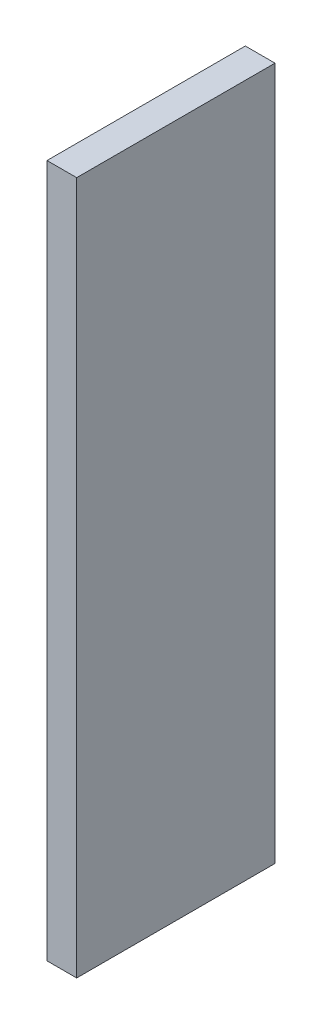
SolidWorks part; units mm, degrees
ref_plane "Front Plane" through (0, 0, 0) normal (0, 0, 1) x (1, 0, 0)
ref_plane "Top Plane" through (0, 0, 0) normal (0, 1, 0) x (1, 0, 0)
ref_plane "Right Plane" through (0, 0, 0) normal (1, 0, 0) x (0, 0, -1)
sketch "Sketch1" plane through (0, 0, 0) normal (1, 0, 0) x (0, 0, -1)
  line L0 (20.0425, 0) -> (20.0425, 6.4639)
  line L1 (0, 0) -> (20.0425, 0)
  line L2 (0, 0) -> (0, 70.0425)
  line L3 (0, 70.0425) -> (20.0425, 70.0425)
  line L9 (20.0425, 6.4639) -> (20.0425, 70.0425)
extrude "Boss-Extrude1" add sketch "Sketch1" along normal blind 3
